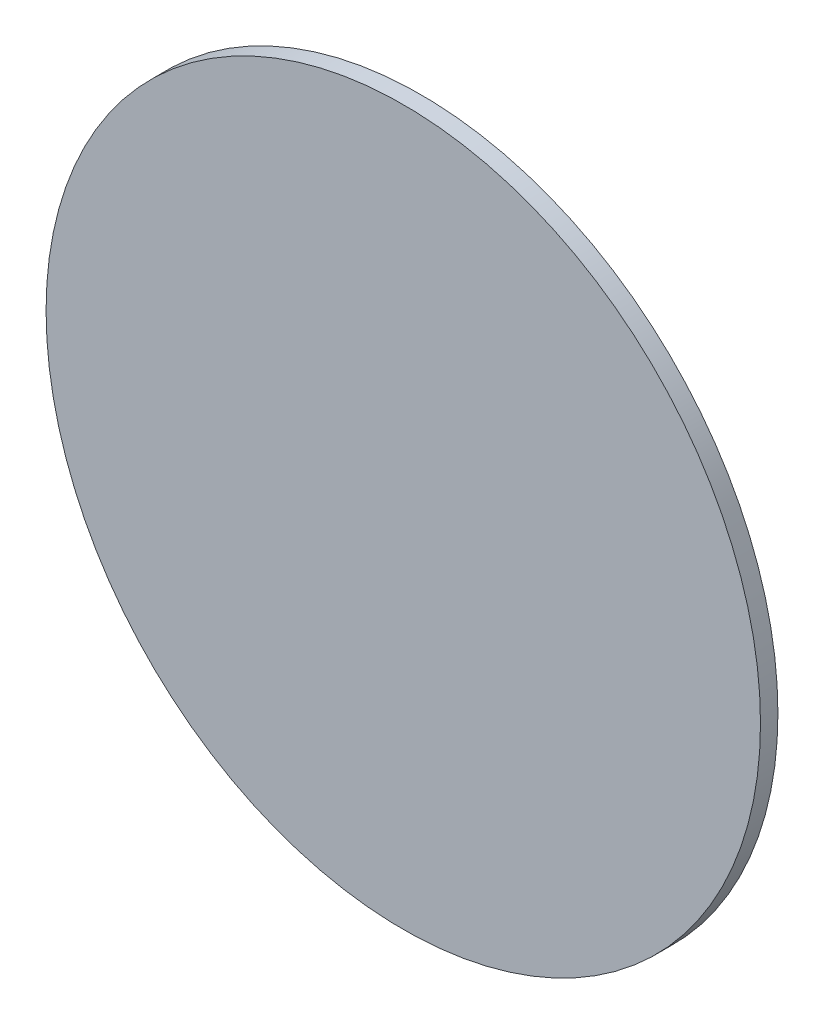
SolidWorks part; units mm, degrees
ref_plane "前视基准面" through (0, 0, 0) normal (0, 0, 1) x (1, 0, 0)
ref_plane "上视基准面" through (0, 0, 0) normal (0, 1, 0) x (1, 0, 0)
ref_plane "右视基准面" through (0, 0, 0) normal (1, 0, 0) x (0, 0, -1)
sketch "草图1" plane through (0, 0, 0) normal (0, 0, 1) x (1, 0, 0)
  circle A0 centre (0, 0) radius 4.1
  dimension "D1" = 8.2
extrude "凸台-拉伸1" add sketch "草图1" along normal blind 0.2
